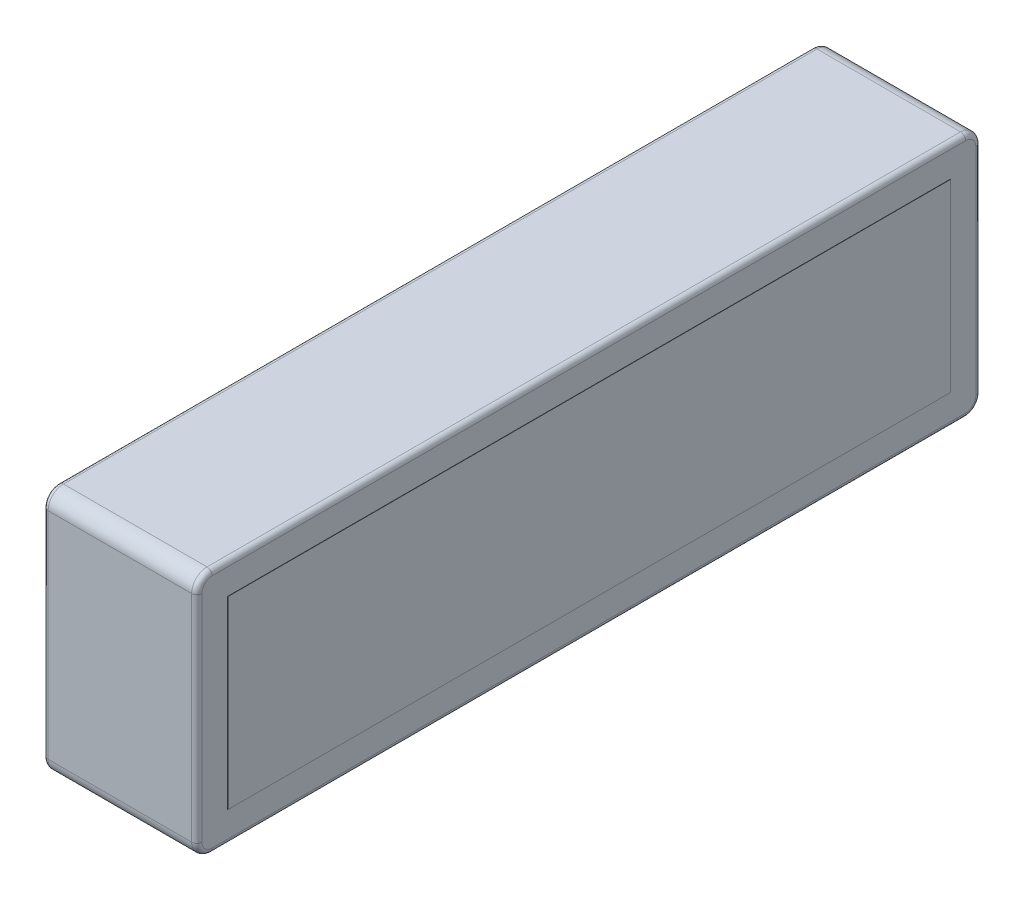
SolidWorks part; units mm, degrees
ref_plane "Front Plane" through (0, 0, 0) normal (0, 0, 1) x (1, 0, 0)
ref_plane "Top Plane" through (0, 0, 0) normal (0, 1, 0) x (1, 0, 0)
ref_plane "Right Plane" through (0, 0, 0) normal (1, 0, 0) x (0, 0, -1)
sketch "Sketch1" plane through (0, 0, 0) normal (0, 0, 1) x (1, 0, 0)
  line L1 (-15, 24) -> (15, 24)
  line L2 (-15, 24) -> (-15, -24)
  line L3 (-15, -24) -> (15, -24)
  line L4 (15, 24) -> (15, -24)
  line L5 (-15, 24) -> (15, -24) construction
  line L6 (-15, -24) -> (15, 24) construction
  point P0 (0, 0)
  dimension "D1" = 30
  dimension "D2" = 48
extrude "Boss-Extrude1" add sketch "Sketch1" along normal blind 153
fillet "Fillet1" radius 3 4 edges at (0, -24, 153) (0, -24, 0) (0, 24, 0) (0, 24, 153)
fillet "Fillet2" radius 1 16 edges at (-15, -23.1213, 0.8787) (-15, 0, 0) (-15, 23.1213, 0.8787) (-15, 24, 76.5) (-15, 23.1213, 152.1213) (-15, 0, 153) (-15, -23.1213, 152.1213) (-15, -24, 76.5) (15, 23.1213, 152.1213) (15, 24, 76.5) (15, 23.1213, 0.8787) (15, 0, 0) (15, -23.1213, 0.8787) (15, -24, 76.5) (15, -23.1213, 152.1213) (15, 0, 153)
sketch "Sketch2" plane through (-15, 0, 0) normal (-1, 0, 0) x (0, 0, 1)
  line L8 (6, 18) -> (6, -18)
  line L9 (6, -18) -> (147, -18)
  line L10 (147, -18) -> (147, 18)
  line L11 (147, 18) -> (6, 18)
  line L12 (6, 18) -> (6, -18)
  line L13 (6, -18) -> (147, -18)
  line L14 (147, -18) -> (147, 18)
  line L15 (147, 18) -> (6, 18)
  dimension "D1" = 5
extrude "Boss-Extrude2" add sketch "Sketch2" along normal blind 0.05
mirror "Mirror1" about plane through (0, 0, 0) normal (1, 0, 0) of "Boss-Extrude2"
